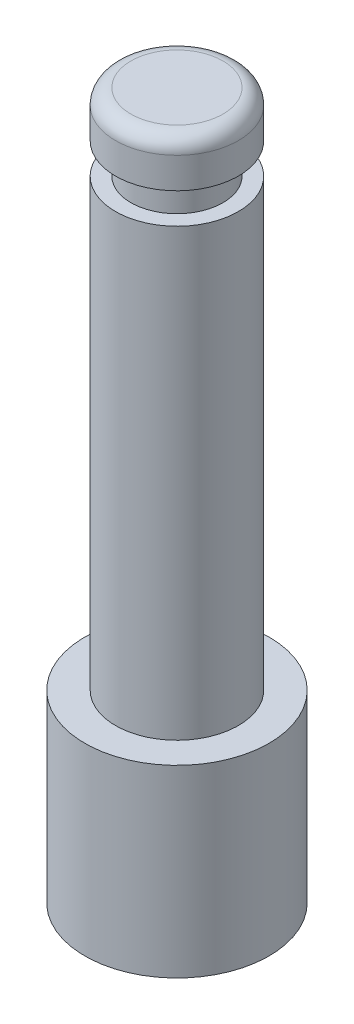
SolidWorks part; units mm, degrees
ref_plane "Plan de face" through (0, 0, 0) normal (0, 0, 1) x (1, 0, 0)
ref_plane "Plan de dessus" through (0, 0, 0) normal (0, 1, 0) x (1, 0, 0)
ref_plane "Plan de droite" through (0, 0, 0) normal (1, 0, 0) x (0, 0, -1)
sketch "Esquisse1" plane through (0, 0, 0) normal (0, 0, 1) x (1, 0, 0)
  line L0 (0, 0) -> (0, 31.4158) construction
  line L1 (0, 0) -> (1.5, 0)
  line L2 (1.5, 0) -> (1.5, 3)
  line L3 (1.5, 3) -> (1, 3)
  line L4 (1, 3) -> (1, 10.25)
  line L5 (0.75, 11.5) -> (0, 11.5)
  line L6 (0, 11.5) -> (0, 0)
  line L7 (1, 10.75) -> (0.75, 10.75)
  line L8 (0.75, 10.75) -> (0.75, 10.25)
  line L9 (0.75, 10.25) -> (1, 10.25)
  line L10 (1, 10.75) -> (1, 11.25)
  arc A0 (0.75, 11.5) -> (1, 11.25) centre (0.75, 11.25) cw
  dimension "D8" = 0.25
  dimension "D1" = 1
  dimension "D2" = 1.5
  dimension "D3" = 3
  dimension "D4" = 0.75
  dimension "D5" = 7.25
  dimension "D6" = 0.5
  dimension "D7" = 0.25
revolve "Révolution1" add sketch "Esquisse1" angle 360 about L0
